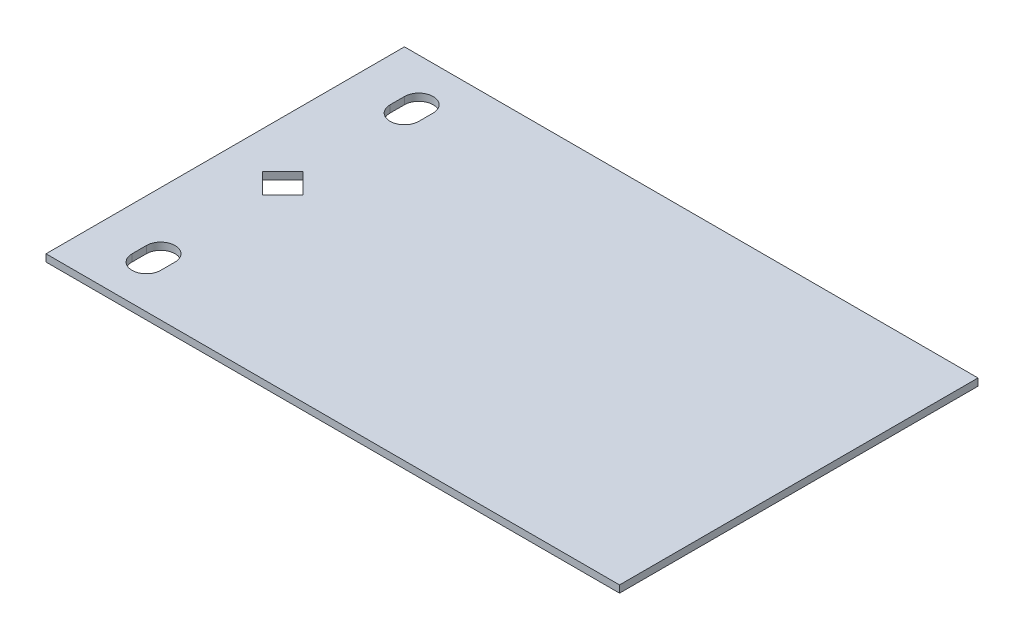
SolidWorks part; units mm, degrees
ref_plane "Спереди" through (0, 0, 0) normal (0, 0, 1) x (1, 0, 0)
ref_plane "Сверху" through (0, 0, 0) normal (0, 1, 0) x (1, 0, 0)
ref_plane "Справа" through (0, 0, 0) normal (1, 0, 0) x (0, 0, -1)
sketch "Эскиз1" plane through (0, 0, 0) normal (0, 1, 0) x (1, 0, 0)
  line L0 (-1000, 0) -> (49000, 0) construction
  line L1 (-40, -25) -> (40, -25)
  line L2 (-40, -25) -> (-40, 25)
  line L3 (-40, 25) -> (40, 25)
  line L4 (40, -25) -> (40, 25)
  line L5 (-40, -25) -> (40, 25) construction
  line L6 (-40, 25) -> (40, -25) construction
  line L7 (-34, -1000) -> (-34, 49000) construction
  line L8 (-34.8284, 0) -> (-32, -2.8284)
  line L9 (-32, -2.8284) -> (-29.1716, 0)
  line L10 (-29.1716, 0) -> (-32, 2.8284)
  line L11 (-32, 2.8284) -> (-34.8284, 0)
  line L12 (-32, -1000) -> (-32, 49000) construction
  line L13 (-30, -19) -> (-30, -17)
  line L14 (-34, -18) -> (-30, -18) construction
  line L15 (-34, -17) -> (-30, -17) construction
  line L16 (-34, -19) -> (-34, -17)
  line L17 (-34, 19) -> (-34, 17)
  line L18 (-30, 19) -> (-30, 17)
  circle A0 centre (-32, 0) radius 2 construction
  circle A1 centre (-32, -18) radius 2 construction
  arc A2 (-34, -17) -> (-30, -17) centre (-32, -17) cw
  arc A3 (-34, -19) -> (-30, -19) centre (-32, -19) ccw
  circle A4 centre (-32, 18) radius 2 construction
  arc A5 (-34, 19) -> (-30, 19) centre (-32, 19) cw
  arc A6 (-34, 17) -> (-30, 17) centre (-32, 17) ccw
  point P0 (0, 0)
  dimension "D3" = 4
  dimension "D1" = 50
  dimension "D2" = 80
  dimension "D4" = 8
  dimension "D5" = 18
  dimension "D6" = 1
extrude "Бобышка-Вытянуть2" add sketch "Эскиз1" along normal blind 1
